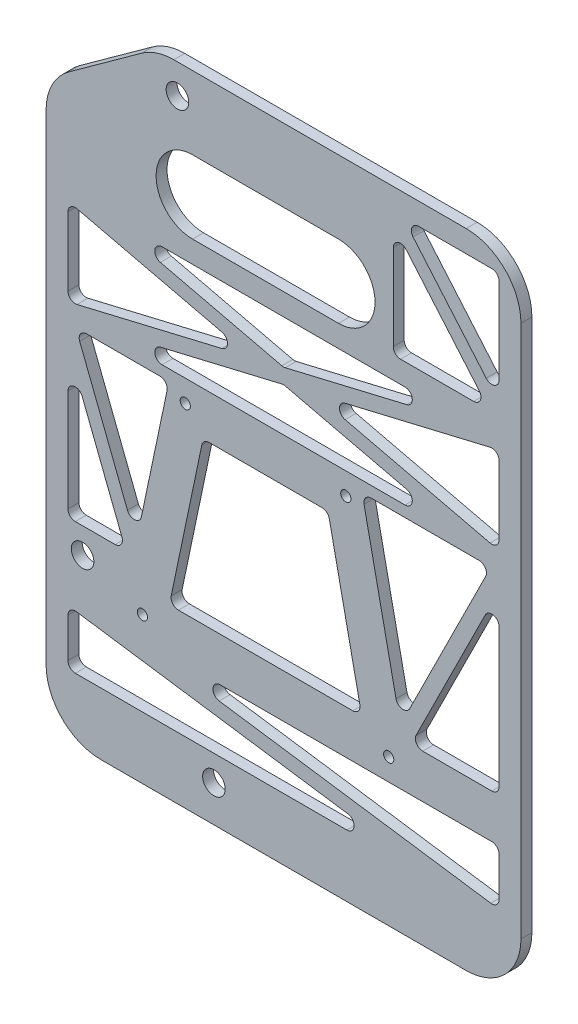
SolidWorks part; units mm, degrees
material "Thornel Mat VMA"
ref_plane "前视基准面" through (0, 0, 0) normal (0, 0, 1) x (1, 0, 0)
ref_plane "上视基准面" through (0, 0, 0) normal (0, 1, 0) x (1, 0, 0)
ref_plane "右视基准面" through (0, 0, 0) normal (1, 0, 0) x (0, 0, -1)
other "Configuration Table"
sketch "草图1" plane through (0, 0, 0) normal (0, 0, 1) x (1, 0, 0)
  line L0 (16.3951, -5.8932) -> (83.8951, -5.8932) construction
  line L1 (28.1451, 50.1068) -> (72.1451, 50.1068) construction
  line L2 (50.1451, 50.1068) -> (50.1451, -5.8932) construction
  line L3 (26, 122) -> (0, 103.2223) construction
  line L4 (0, 103.2223) -> (0, 0) construction
  line L5 (0, 0) -> (0, -36) construction
  line L6 (0, -36) -> (36, -36) construction
  line L7 (20.1451, 130.1068) -> (-10, 108.3354)
  line L8 (-10, 108.3354) -> (-10, 0)
  line L9 (-10, 0) -> (-10, -46)
  line L10 (-10, -46) -> (36, -46)
  line L11 (31.8549, 113.8932) -> (10, 98.1091)
  line L12 (10, 98.1091) -> (10, 0)
  line L13 (10, 0) -> (10, -26)
  line L14 (10, -26) -> (36, -26)
  line L15 (20.1451, 130.1068) -> (120.1451, 130.1068)
  line L16 (120.1451, 130.1068) -> (120.1451, -46)
  line L17 (120.1451, -46) -> (36, -46)
  line L18 (50.1451, 50.1068) -> (50.1451, 130.1068) construction
  line L19 (30.1451, 100.1068) -> (70.1451, 100.1068) construction
  line L20 (30.1451, 110.1068) -> (70.1451, 110.1068)
  line L21 (30.1451, 90.1068) -> (70.1451, 90.1068)
  circle A0 centre (0, 0) radius 3.1
  circle A1 centre (26, 122) radius 3.1
  circle A2 centre (36, -36) radius 3.1
  circle A3 centre (28.1451, 50.1068) radius 1.4
  circle A4 centre (72.1451, 50.1068) radius 1.4
  circle A5 centre (16.3951, -5.8932) radius 1.4
  circle A6 centre (83.8951, -5.8932) radius 1.4
  arc A7 (30.1451, 110.1068) -> (30.1451, 90.1068) centre (30.1451, 100.1068) ccw
  arc A8 (70.1451, 90.1068) -> (70.1451, 110.1068) centre (70.1451, 100.1068) ccw
  point P10 (50.1451, -5.8932)
  point P13 (50.1451, 50.1068)
  point P36 (50.1451, 100.1068)
  dimension "D1" = 26
  dimension "D2" = 122
  dimension "D3" = 36
  dimension "D4" = 36
  dimension "D5" = 6.2
  dimension "D9" = 2.8
  dimension "D16" = 10
  dimension "D6" = 44
  dimension "D7" = 67.5
  dimension "D8" = 56
  dimension "D10" = 125.838
  dimension "D13" = 100
  dimension "D14" = 70
  dimension "D15" = 40
  dimension "D17" = 30
  dimension "D18" = 80
  dimension "D11" = 10
  dimension "D12" = 10
extrude "凸台-拉伸1" add sketch "草图1" along normal blind 3
fillet "圆角1" radius 15 5 edges at (-10, 108.3354, 1.5) (20.1451, 130.1068, 1.5) (120.1451, 130.1068, 1.5) (120.1451, -46, 1.5) (-10, -46, 1.5)
sketch "草图2" plane through (0, 0, 3) normal (0, 0, 1) x (1, 0, 0)
  line L0 (28.1451, 50.1068) -> (72.1451, 50.1068) construction
  line L1 (72.1451, 50.1068) -> (83.8951, -5.8932) construction
  line L2 (83.8951, -5.8932) -> (16.3951, -5.8932) construction
  line L3 (16.3951, -5.8932) -> (28.1451, 50.1068) construction
  line L4 (33.0168, 44.1068) -> (67.2734, 44.1068)
  line L5 (67.2734, 44.1068) -> (76.5055, 0.1068)
  line L6 (76.5055, 0.1068) -> (23.7847, 0.1068)
  line L7 (23.7847, 0.1068) -> (33.0168, 44.1068)
  line L8 (-10, 34.8328) -> (120.1451, 34.8328) construction
  line L9 (-4, 56.1068) -> (114.1451, 56.1068)
  line L10 (-4, 56.1068) -> (-4, 84.1068)
  line L11 (-4, 84.1068) -> (114.1451, 84.1068)
  line L12 (114.1451, 56.1068) -> (114.1451, 84.1068)
  line L13 (-4, 56.1068) -> (114.1451, 84.1068) construction
  line L14 (-4, 84.1068) -> (114.1451, 56.1068) construction
  line L15 (-10, 100.6657) -> (-10, -31) construction
  line L16 (120.1451, 115.1068) -> (120.1451, -31) construction
  line L17 (55.0726, 34.8328) -> (55.0726, -49965.1672) construction
  line L18 (23.6657, 53.1068) -> (13.9915, 7)
  line L19 (13.9915, 7) -> (-4, 7)
  line L20 (-4, 7) -> (-4, 53.1068)
  line L21 (-4, 53.1068) -> (23.6657, 53.1068)
  line L22 (30.1451, 90.1068) -> (70.1451, 90.1068) construction
  line L23 (76.6245, 53.1068) -> (114.1451, 53.1068)
  line L24 (114.1451, 53.1068) -> (114.1451, 0.1068)
  line L25 (114.1451, 0.1068) -> (87.7451, 0.1068)
  line L26 (87.7451, 0.1068) -> (76.6245, 53.1068)
  line L27 (-4, 53.1068) -> (13.9915, 7) construction
  line L28 (114.1451, 53.1068) -> (87.7451, 0.1068) construction
  line L29 (24.9954, 130.1068) -> (105.1451, 130.1068) construction
  line L30 (-4, -29) -> (114.1451, -29)
  line L31 (-4, -29) -> (-4, -11.8932)
  line L32 (-4, -11.8932) -> (114.1451, -11.8932)
  line L33 (114.1451, -29) -> (114.1451, -11.8932)
  line L34 (-4, -29) -> (114.1451, -11.8932) construction
  line L35 (-4, -11.8932) -> (114.1451, -29) construction
  line L36 (85.1451, 90.1068) -> (114.1451, 90.1068)
  line L37 (85.1451, 90.1068) -> (85.1451, 124.1068)
  line L38 (85.1451, 124.1068) -> (114.1451, 124.1068)
  line L39 (114.1451, 90.1068) -> (114.1451, 124.1068)
  line L40 (85.1451, 90.1068) -> (114.1451, 124.1068) construction
  line L41 (85.1451, 124.1068) -> (114.1451, 90.1068) construction
  line L42 (112.3549, 53.9985) -> (85.9548, 0.9985)
  line L43 (-5.8632, 52.3798) -> (12.1283, 6.273)
  line L44 (-4.4612, 82.1607) -> (113.6839, 54.1607)
  line L45 (-3.5388, 54.1607) -> (114.6063, 82.1607)
  line L46 (83.6234, 122.8089) -> (112.6234, 88.8089)
  line L47 (-4.2866, -13.8726) -> (113.8585, -30.9794)
  line L48 (115.9353, 52.2151) -> (89.5353, -0.7849)
  line L49 (-2.1368, 53.8338) -> (15.8547, 7.727)
  line L50 (-3.5388, 86.0529) -> (114.6063, 58.0529)
  line L51 (-4.4612, 58.0529) -> (113.6839, 86.0529)
  line L52 (86.6668, 125.4047) -> (115.6668, 91.4047)
  line L53 (-3.7134, -9.9138) -> (114.4317, -27.0206)
  circle A0 centre (0, 0) radius 3.1 construction
  circle A1 centre (36, -36) radius 3.1 construction
  arc A2 (70.1451, 90.1068) -> (70.1451, 110.1068) centre (70.1451, 100.1068) ccw construction
  point P12 (55.0726, 70.1068)
  point P25 (55.0726, 34.8328)
  point P33 (55.0726, -20.4466)
  point P45 (99.6451, 107.1068)
  dimension "D6" = 7
  dimension "D11" = 15
  dimension "D1" = 6
  dimension "D2" = 6
  dimension "D3" = 6
  dimension "D4" = 6
  dimension "D5" = 3
  dimension "D7" = 5
  dimension "D8" = 5
  dimension "D9" = 6
  dimension "D10" = 7
  dimension "D12" = 6
  dimension "D13" = 6
  dimension "D14" = 2
  dimension "D15" = 2
extrude "切除-拉伸1" cut sketch "草图2" against normal blind 10 contours L32 L53 L33 | L47 L31 L30 | L7 L6 L5 L4 | L21 L49 L18 | L43 L20 L19 | L42 L23 L26 | L24 L48 L25 | L10 L51 L44 | L50 L51 L11 | L45 L50 L12 | L45 L9 L44 | L38 L52 L39 | L46 L37 L36
fillet "圆角2" radius 2 40 edges at (-4, 82.0514, 1.5) (46.3999, 70.1068, 1.5) (-4, 58.1622, 1.5) (105.4724, 84.1068, 1.5) (55.0726, 72.1622, 1.5) (4.6727, 84.1068, 1.5) (114.1451, 0.1068, 1.5) (89.9794, 0.1068, 1.5) (114.1451, 48.6211, 1.5) (33.0168, 44.1068, 1.5) (67.2734, 44.1068, 1.5) (76.5055, 0.1068, 1.5) (23.7847, 0.1068, 1.5) (23.6657, 53.1068, 1.5) (14.7422, 10.5779, 1.5) (-1.8531, 53.1068, 1.5) (114.1451, 82.0514, 1.5) (114.1451, 58.1622, 1.5) (63.7452, 70.1068, 1.5) (114.1451, 124.1068, 1.5) (114.1451, 93.1887, 1.5) (87.7738, 124.1068, 1.5) (114.1451, -11.8932, 1.5) (114.1451, -26.9791, 1.5) (9.9567, -11.8932, 1.5) (111.5164, 90.1068, 1.5) (85.1451, 121.0249, 1.5) (55.0726, 68.0514, 1.5) (105.4724, 56.1068, 1.5) (4.6727, 56.1068, 1.5) (11.8446, 7, 1.5) (-4, 7, 1.5) (-4, 47.605, 1.5) (100.1884, -29, 1.5) (-4, -29, 1.5) (-4, -13.9141, 1.5) (87.0828, 3.263, 1.5) (76.6245, 53.1068, 1.5) (111.9107, 53.1068, 1.5) (85.1451, 90.1068, 1.5)
